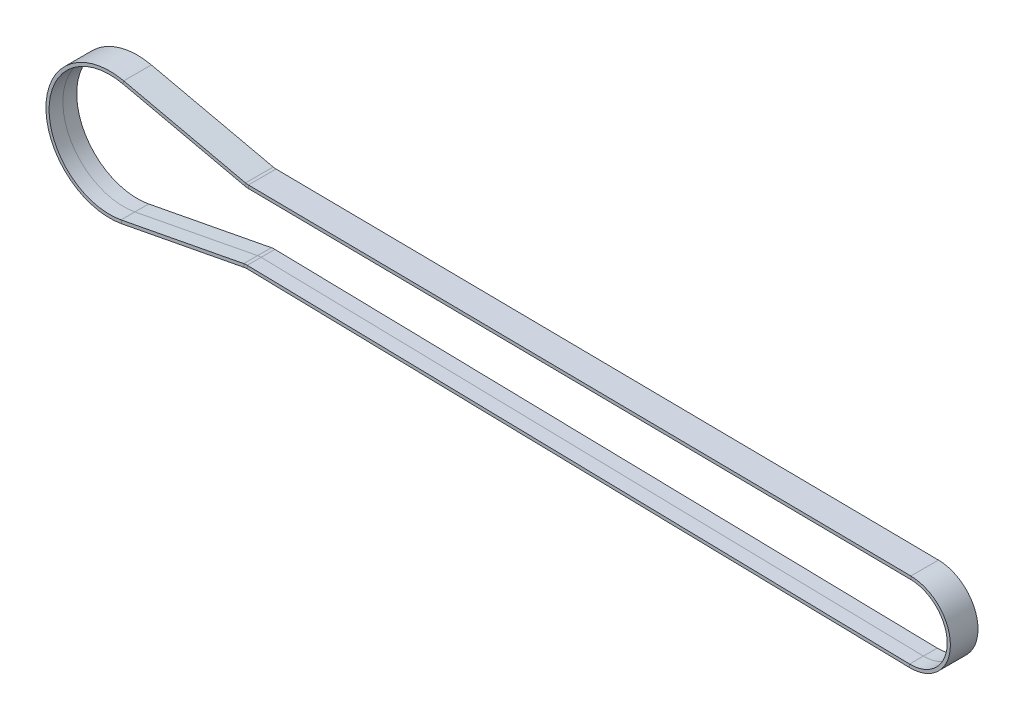
SolidWorks part; units mm, degrees
material "Rubber"
ref_plane "Front Plane" through (0, 0, 0) normal (0, 0, 1) x (1, 0, 0)
ref_plane "Top Plane" through (0, 0, 0) normal (0, 1, 0) x (1, 0, 0)
ref_plane "Right Plane" through (0, 0, 0) normal (1, 0, 0) x (0, 0, -1)
sketch "Sketch2" plane through (0, 0, 0) normal (0, 0, 1) x (1, 0, 0)
  line L0 (0, 0) -> (1, 0) construction
  line L1 (0, 0) -> (0, 1) construction
  line L2 (-0.0681, -6.0696) -> (239.8211, -8.7625)
  line L3 (239.3857, -35.4586) -> (-0.4638, -30.3265)
  line L4 (-1.7352, -30.4335) -> (-46.1621, -38.9405)
  line L5 (-45.4612, 4.0301) -> (-1.3354, -5.9213)
  arc A0 (-1.3354, -5.9213) -> (-0.0681, -6.0696) centre (0, 0) ccw
  arc A1 (239.8211, -8.7625) -> (239.3857, -35.4586) centre (239.6713, -22.1117) cw
  arc A2 (-0.4638, -30.3265) -> (-1.7352, -30.4335) centre (-0.5936, -36.3952) ccw
  arc A3 (-46.1621, -38.9405) -> (-45.4612, 4.0301) centre (-50.2902, -17.3821) cw
ref_plane "Plane1" through (-45.4612, 4.0301, 0) normal (-0.9755, 0.22, 0) x (0, 0, 1)
sketch "Sketch5" plane through (-45.4612, 4.0301, 0) normal (-0.9755, 0.22, 0) x (0, 0, 1)
  line L0 (0, 0) -> (5, 0)
  line L1 (0, -43.9) -> (0, 0) construction
  line L2 (0, 24.1444) -> (0, -23.6156) construction
  line L3 (5, 0) -> (5, 1.14)
  line L4 (5, 1.14) -> (-5, 1.14)
  line L5 (-5, 1.14) -> (-5, 0)
  line L6 (-5, 0) -> (0, 0)
  dimension "D1" = 5
  dimension "D2" = 1.14
  dimension "D3" = 10
sweep "Sweep1" add profiles "Sketch5" path "Sketch2"
